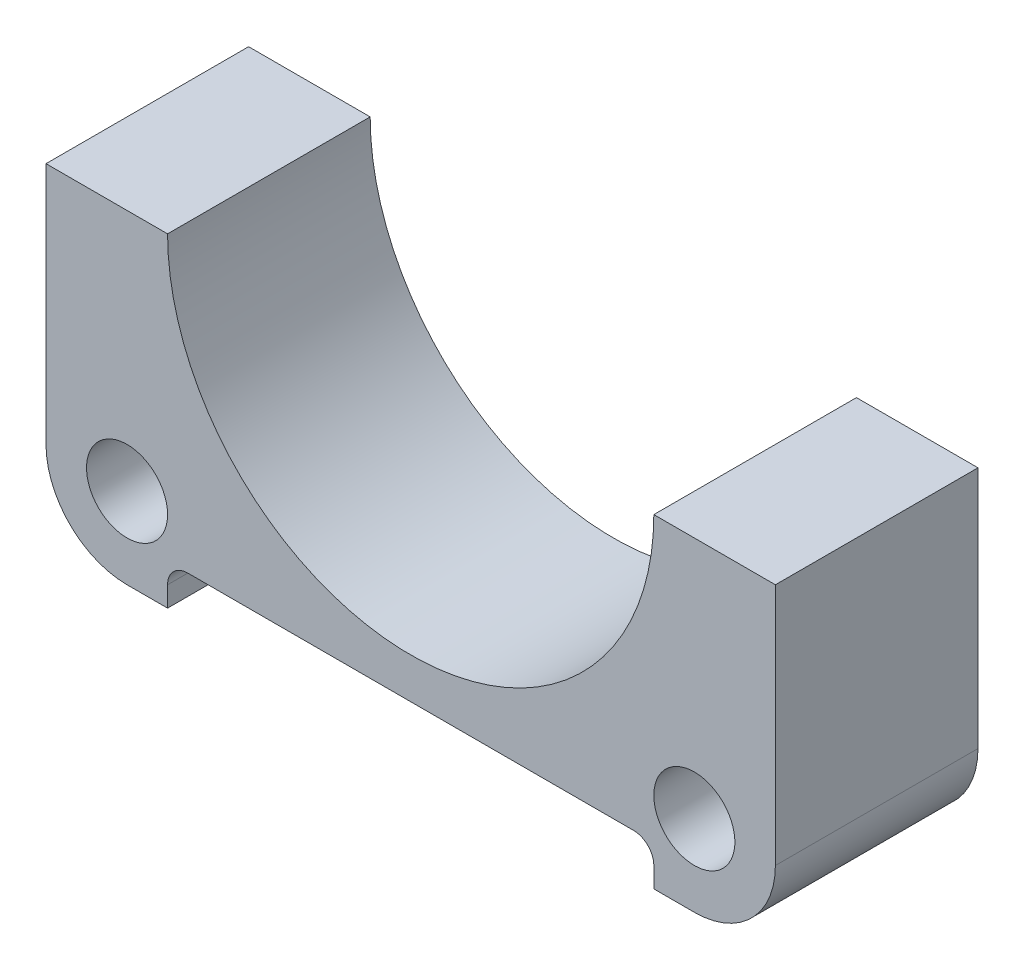
SolidWorks part; units mm, degrees
ref_plane "Front Plane" through (0, 0, 0) normal (0, 0, 1) x (1, 0, 0)
ref_plane "Top Plane" through (0, 0, 0) normal (0, 1, 0) x (1, 0, 0)
ref_plane "Right Plane" through (0, 0, 0) normal (1, 0, 0) x (0, 0, -1)
sketch "Sketch2" plane through (0, 0, 0) normal (0, 0, 1) x (1, 0, 0)
  line L0 (0, 85.3335) -> (0, -85.3335) construction
  line L1 (-60, 0) -> (-90, 0)
  line L2 (-90, 0) -> (-90, -7.7237)
  line L3 (-90, -7.7237) -> (-90, -60)
  line L4 (-70, -80) -> (-60, -80)
  line L5 (-60, -80) -> (-60, -75)
  line L6 (-55, -70) -> (55, -70)
  line L7 (60, -80) -> (60, -75)
  line L8 (70, -80) -> (60, -80)
  line L9 (90, -7.7237) -> (90, -60)
  line L10 (90, 0) -> (90, -7.7237)
  line L11 (60, 0) -> (90, 0)
  arc A0 (-60, 0) -> (60, 0) centre (0, 0) ccw
  arc A1 (-70, -80) -> (-90, -60) centre (-70, -60) cw
  circle A2 centre (-70, -60) radius 10
  arc A3 (-60, -75) -> (-55, -70) centre (-55, -75) cw
  arc A4 (60, -75) -> (55, -70) centre (55, -75) ccw
  circle A5 centre (70, -60) radius 10
  arc A6 (70, -80) -> (90, -60) centre (70, -60) ccw
  point P1 (0, -70)
  point P9 (-60, -77.5)
  dimension "D1" = 120
  dimension "D6" = 20
  dimension "D7" = 20
  dimension "D2" = 80
  dimension "D3" = 180
  dimension "D4" = 10
  dimension "D5" = 120
extrude "Boss-Extrude1" add sketch "Sketch2" along normal blind 50
